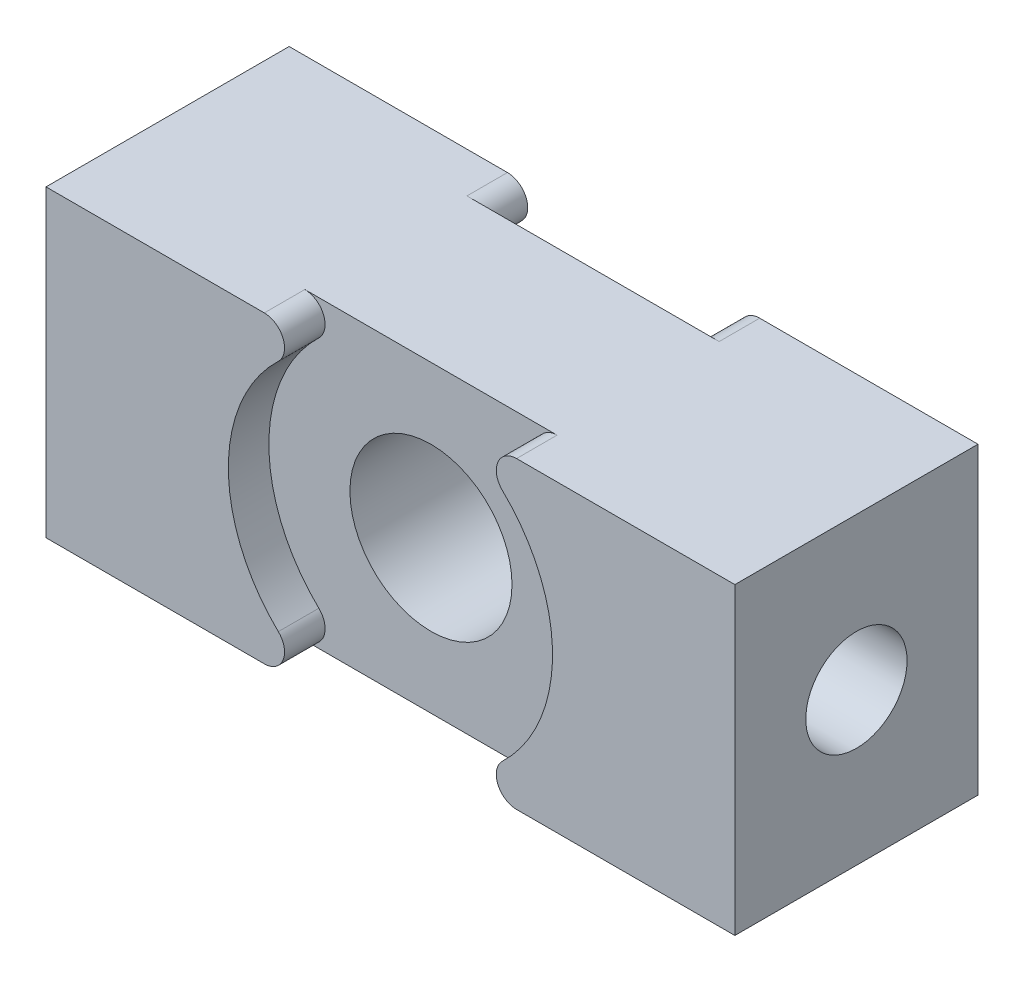
SolidWorks part; units mm, degrees
ref_plane "Front Plane" through (0, 0, 0) normal (0, 0, 1) x (1, 0, 0)
ref_plane "Top Plane" through (0, 0, 0) normal (0, 1, 0) x (1, 0, 0)
ref_plane "Right Plane" through (0, 0, 0) normal (1, 0, 0) x (0, 0, -1)
other "Configuration Table"
sketch "草图1" plane through (0, 0, 0) normal (0, 1, 0) x (1, 0, 0)
  line L1 (-17, 6) -> (17, 6)
  line L2 (-17, 6) -> (-17, -6)
  line L3 (-17, -6) -> (17, -6)
  line L4 (17, 6) -> (17, -6)
  line L5 (-17, 6) -> (17, -6) construction
  line L6 (-17, -6) -> (17, 6) construction
  point P0 (0, 0)
extrude "凸台-拉伸1" add sketch "草图1" along normal blind 15
sketch "草图2" plane through (0, 0, -6) normal (0, 0, -1) x (-1, 0, 0)
  line L0 (0, 0) -> (0, 7.5) construction
  circle A0 centre (0, 7.5) radius 4
  dimension "D1" = 8
extrude "切除-拉伸1" cut sketch "草图2" against normal through all
sketch "草图5" plane through (-17, 0, 0) normal (-1, 0, 0) x (0, 0, 1)
  line L0 (0, 15) -> (0, 0) construction
  line L1 (-6, 15) -> (6, 15) construction
  line L2 (-6, 0) -> (6, 0) construction
  point P7 (0, 7.5)
hole_wizard "M6x1.0 螺纹孔2" positions "草图5" profile "草图6" tap size "M6x1.0" standard "ANSI Metric"
sketch "草图6" plane through (-17, 7.5, 0) normal (0, 1, 0) x (0, 0, 1)
  line L0 (0, 0) -> (0, 11.5022)
  line L1 (0, 11.5022) -> (2.5, 10)
  line L2 (2.5, 10) -> (2.5, 0)
  line L5 (2.5, 0) -> (0, 0)
  line L10 (0, 11.5022) -> (-2.5, 10) construction
  line L11 (0, -6.35) -> (0, 107.95) construction
  dimension "螺纹孔钻头直径" = 5
  dimension "螺纹孔钻头深度" = 10
  dimension "导头角度" = 118
cosmetic thread "孔螺纹线1" parameters "D1"=12, "D2"=6
sketch "草图7" plane through (17, 0, 0) normal (1, 0, 0) x (0, 0, -1)
  line L0 (0, 15) -> (0, 0) construction
  line L1 (-6, 15) -> (6, 15) construction
sketch "草图10" plane through (17, 0, 0) normal (1, 0, 0) x (0, 0, -1)
  line L0 (0, 15) -> (0, 0) construction
  point P0 (0, 7.5)
hole_wizard "M6x1.0 螺纹孔1" positions "草图10" profile "草图9" tap size "M6x1.0" standard "ANSI Metric"
sketch "草图9" plane through (17, 7.5, 0) normal (0, 1, 0) x (0, 0, -1)
  line L0 (0, 0) -> (0, 11.5022)
  line L1 (0, 11.5022) -> (2.5, 10)
  line L2 (2.5, 10) -> (2.5, 0)
  line L5 (2.5, 0) -> (0, 0)
  line L10 (0, 11.5022) -> (-2.5, 10) construction
  line L11 (0, -6.35) -> (0, 107.95) construction
  dimension "螺纹孔钻头直径" = 5
  dimension "螺纹孔钻头深度" = 10
  dimension "导头角度" = 118
cosmetic thread "孔螺纹线2" parameters "D1"=12, "D2"=6
sketch "草图11" plane through (0, 0, 6) normal (0, 0, 1) x (1, 0, 0)
  circle A0 centre (0, 7.5) radius 8
extrude "切除-拉伸2" cut sketch "草图11" against normal blind 2
sketch "草图12" plane through (0, 0, -6) normal (0, 0, -1) x (-1, 0, 0)
  circle A0 centre (0, 7.5) radius 8
extrude "切除-拉伸3" cut sketch "草图12" against normal blind 2
fillet "圆角1" radius 1 8 edges at (2.7839, 0, 5) (-2.7839, 0, 5) (-2.7839, 15, 5) (2.7839, 15, 5) (2.7839, 15, -5) (-2.7839, 15, -5) (2.7839, 0, -5) (-2.7839, 0, -5)
